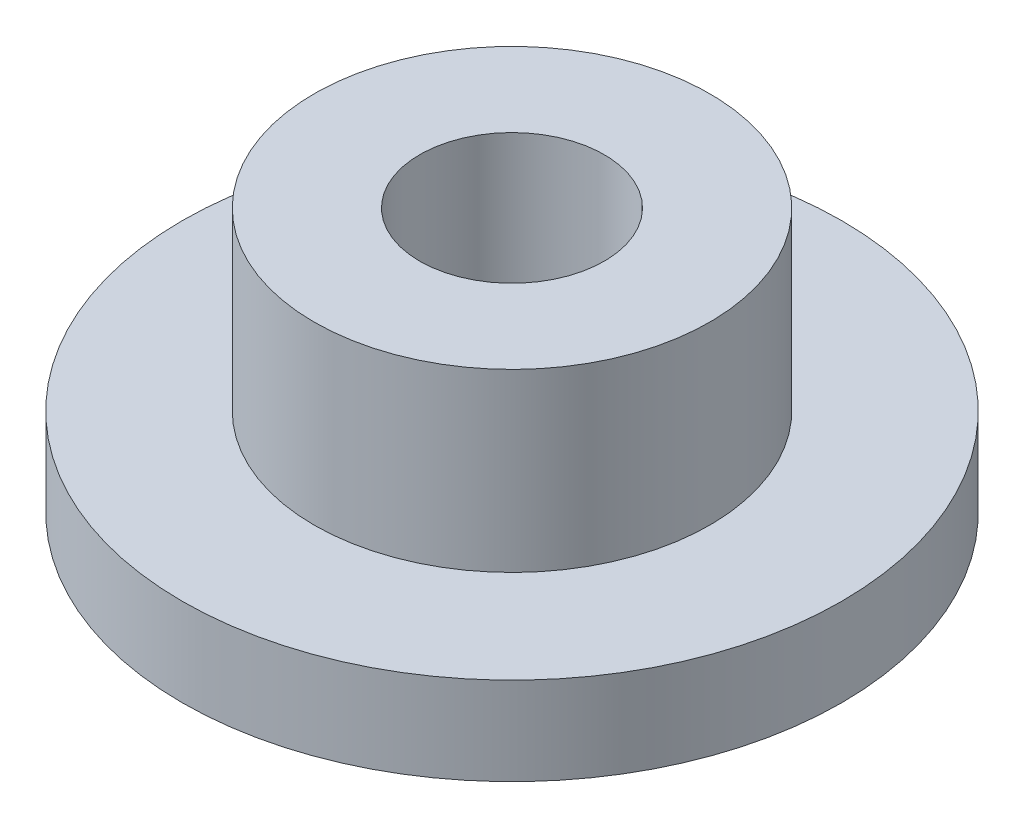
SolidWorks part; units mm, degrees
ref_plane "Front Plane" through (0, 0, 0) normal (0, 0, 1) x (1, 0, 0)
ref_plane "Top Plane" through (0, 0, 0) normal (0, 1, 0) x (1, 0, 0)
ref_plane "Right Plane" through (0, 0, 0) normal (1, 0, 0) x (0, 0, -1)
sketch "Sketch1" plane through (0, 0, 0) normal (0, 1, 0) x (1, 0, 0)
  circle A0 centre (0, 0) radius 3.75
  dimension "D1" = 7.5
extrude "Boss-Extrude1" add sketch "Sketch1" along normal blind 1
sketch "Sketch2" plane through (0, 1, 0) normal (0, 1, 0) x (1, 0, 0)
  circle A0 centre (0, 0) radius 2.25
  dimension "D1" = 4.5
extrude "Boss-Extrude2" add sketch "Sketch2" along normal blind 2
sketch "Sketch3" plane through (0, 3, 0) normal (0, 1, 0) x (1, 0, 0)
  circle A0 centre (0, 0) radius 1.05
  dimension "D1" = 2.1
extrude "Cut-Extrude1" cut sketch "Sketch3" against normal up to surface (3 mm away) up to face at (0, 0, 3.75)
